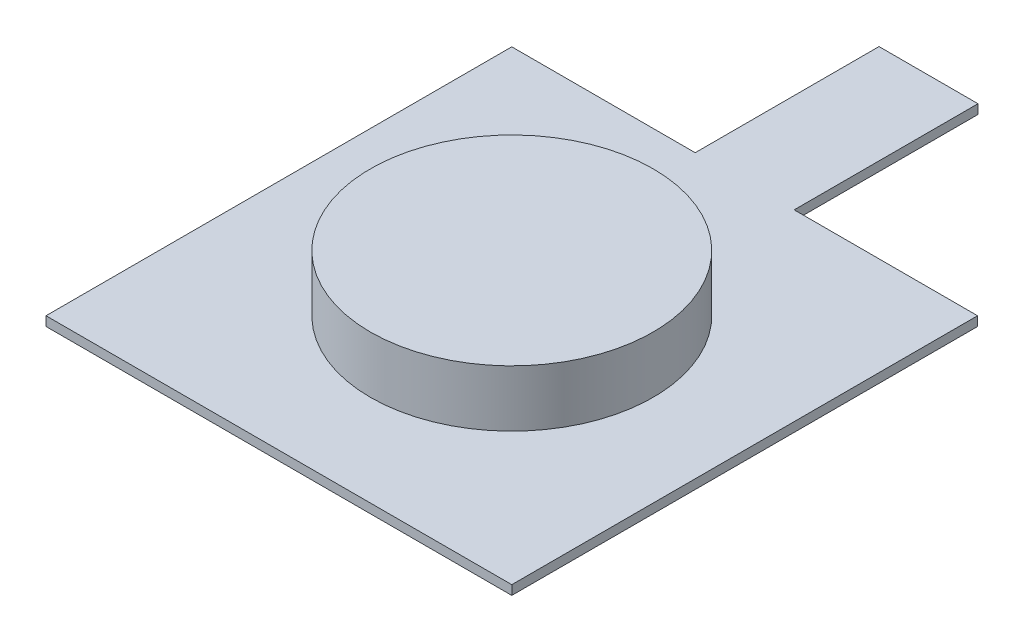
SolidWorks part; units mm, degrees
ref_plane "Front Plane" through (0, 0, 0) normal (0, 0, 1) x (1, 0, 0)
ref_plane "Top Plane" through (0, 0, 0) normal (0, 1, 0) x (1, 0, 0)
ref_plane "Right Plane" through (0, 0, 0) normal (1, 0, 0) x (0, 0, -1)
sketch "Sketch1" plane through (0, 0, 0) normal (0, 1, 0) x (1, 0, 0)
  line L0 (0, 0) -> (16.47, 0)
  line L2 (16.47, 0) -> (16.47, 16.47)
  line L3 (6.485, 16.47) -> (6.485, 22.97)
  line L4 (0, 0) -> (0, 16.47)
  line L5 (6.485, 22.97) -> (9.985, 22.97)
  line L6 (9.985, 22.97) -> (9.985, 16.47)
  line L7 (6.485, 16.47) -> (0, 16.47)
  line L8 (9.985, 16.47) -> (16.47, 16.47)
  dimension "D1" = 3.5
  dimension "D2" = 16.47
  dimension "D3" = 6.5
extrude "Boss-Extrude1" add sketch "Sketch1" along normal blind 0.33
sketch "Sketch2" plane through (0, 0.33, 0) normal (0, 1, 0) x (1, 0, 0)
  line L1 (0, 8.235) -> (16.47, 8.235) construction
  line L2 (0, 16.47) -> (0, 0) construction
  line L3 (16.47, 0) -> (16.47, 16.47) construction
  circle A0 centre (8.235, 8.235) radius 5
  point P8 (0, 0)
  point P9 (8.235, 8.235)
  dimension "D1" = 10
extrude "Boss-Extrude3" add sketch "Sketch2" along normal blind 2
